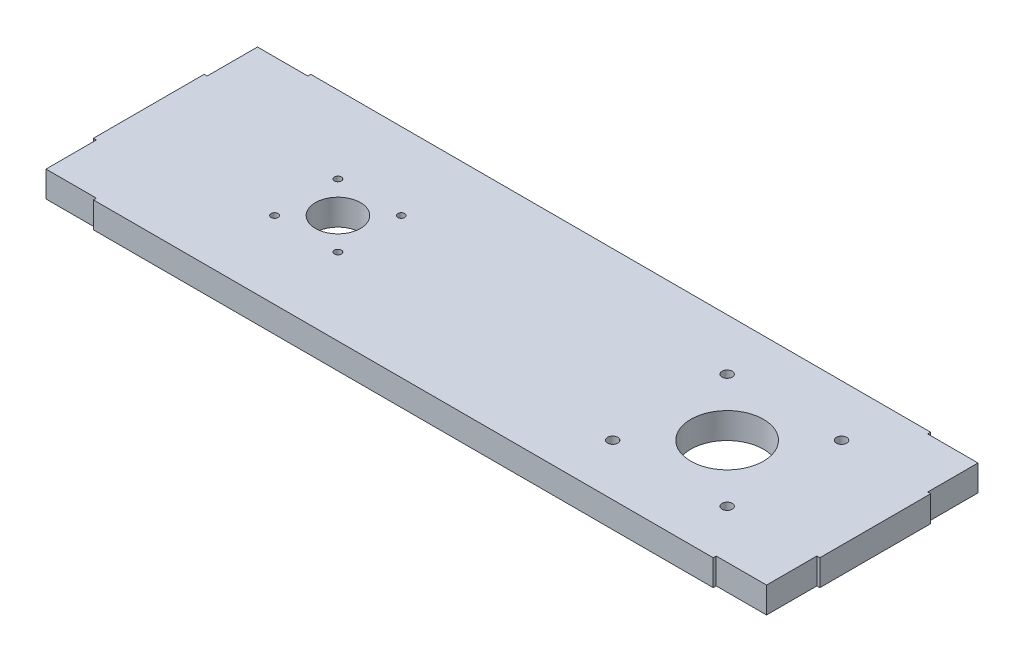
SolidWorks part; units mm, degrees
material "Oak"
ref_plane "Front Plane" through (0, 0, 0) normal (0, 0, 1) x (1, 0, 0)
ref_plane "Top Plane" through (0, 0, 0) normal (0, 1, 0) x (1, 0, 0)
ref_plane "Right Plane" through (0, 0, 0) normal (1, 0, 0) x (0, 0, -1)
sketch "Sketch1" plane through (0, 0, 0) normal (0, 1, 0) x (1, 0, 0)
  line L0 (151.7015, 53.213) -> (151.7015, 51.7525)
  line L1 (-151.7015, 53.213) -> (151.7015, 53.213)
  line L2 (-177.8, 27.1145) -> (-177.8, -27.1145)
  line L3 (-151.7015, -53.213) -> (151.7015, -53.213)
  line L4 (177.8, 27.1145) -> (177.8, -27.1145)
  line L5 (0, -6.985) -> (0, 6.985) construction
  line L6 (-176.3395, 27.1145) -> (-177.8, 27.1145)
  line L7 (151.7015, 51.7525) -> (176.3395, 51.7525)
  line L8 (176.3395, 51.7525) -> (176.3395, 27.1145)
  line L9 (176.3395, 27.1145) -> (177.8, 27.1145)
  line L10 (-176.3395, 51.7525) -> (-176.3395, 27.1145)
  line L11 (-151.7015, 51.7525) -> (-176.3395, 51.7525)
  line L12 (-151.7015, 53.213) -> (-151.7015, 51.7525)
  line L13 (-6.985, 0) -> (6.985, 0) construction
  line L14 (-151.7015, -53.213) -> (-151.7015, -51.7525)
  line L15 (-151.7015, -51.7525) -> (-176.3395, -51.7525)
  line L16 (-176.3395, -51.7525) -> (-176.3395, -27.1145)
  line L17 (-176.3395, -27.1145) -> (-177.8, -27.1145)
  line L18 (176.3395, -27.1145) -> (177.8, -27.1145)
  line L19 (176.3395, -51.7525) -> (176.3395, -27.1145)
  line L20 (151.7015, -51.7525) -> (176.3395, -51.7525)
  line L21 (151.7015, -53.213) -> (151.7015, -51.7525)
  point P0 (0, 0)
  point P4 (0, -53.213)
  point P8 (0, 0)
  point P12 (0, 0)
  point P13 (0, 0)
  point P14 (-177.8, 0)
  dimension "D1" = 355.6
  dimension "D2" = 106.426
  dimension "D3" = 24.638
  dimension "D4" = 1.4605
extrude "Boss-Extrude1" add sketch "Sketch1" along normal blind 12.7
sketch "Sketch2" plane through (0, 12.7, 0) normal (0, 1, 0) x (1, 0, 0)
  line L0 (177.8, -27.1145) -> (177.8, 27.1145) construction
  line L1 (105.3, 53.213) -> (105.3, -53.213) construction
  line L2 (151.7015, 53.213) -> (-151.7015, 53.213) construction
  line L3 (-151.7015, -53.213) -> (151.7015, -53.213) construction
  line L4 (-6.985, 0) -> (6.985, 0) construction
  line L5 (105.3, 0) -> (-85.2, 0) construction
  line L6 (-85.2, 53.213) -> (-85.2, -53.213) construction
  circle A0 centre (133.3, -28) radius 2.5
  circle A1 centre (77.3, -28) radius 2.5
  circle A2 centre (133.3, 28) radius 2.5
  circle A3 centre (77.3, 28) radius 2.5
  circle A4 centre (105.3, 0) radius 17.78
  circle A5 centre (-85.2, 0) radius 11
  circle A6 centre (-100.7, 15.5) radius 1.7
  circle A7 centre (-69.7, 15.5) radius 1.7
  circle A8 centre (-69.7, -15.5) radius 1.7
  circle A9 centre (-100.7, -15.5) radius 1.7
  point P0 (105.3, 0)
  point P28 (-100.7, 16.7468)
  dimension "D4" = 5
  dimension "D5" = 35.56
  dimension "D7" = 22
  dimension "D8" = 3.4
  dimension "D9" = 15.5
  dimension "D1" = 72.5
  dimension "D2" = 28
  dimension "D3" = 28
  dimension "D6" = 190.5
  dimension "D10" = 15.5
extrude "Cut-Extrude1" cut sketch "Sketch2" against normal up to next
